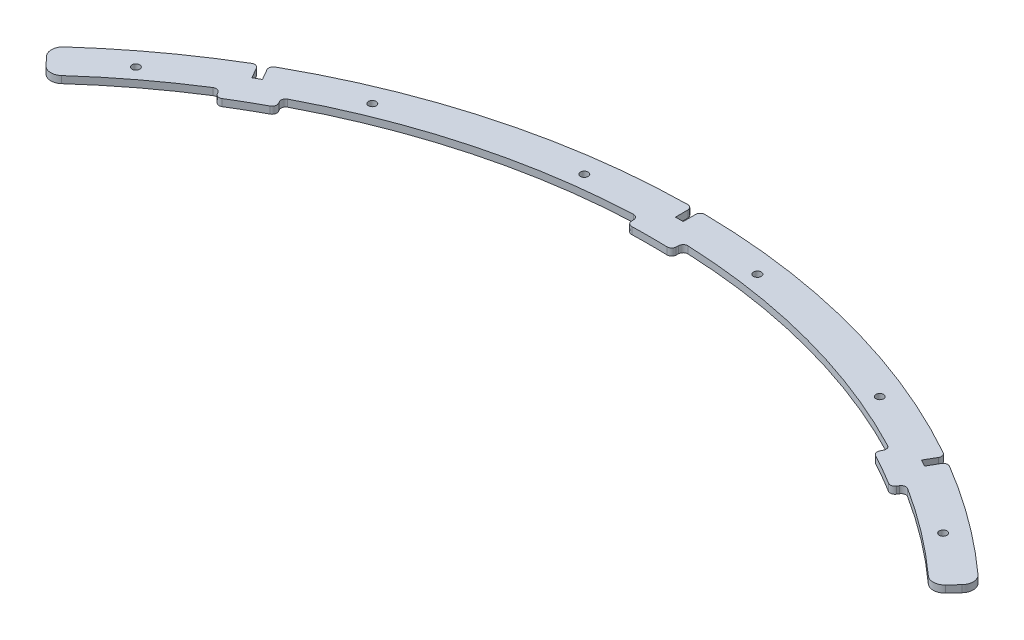
SolidWorks part; units mm, degrees
ref_plane "Front Plane" through (0, 0, 0) normal (0, 0, 1) x (1, 0, 0)
ref_plane "Top Plane" through (0, 0, 0) normal (0, 1, 0) x (1, 0, 0)
ref_plane "Right Plane" through (0, 0, 0) normal (1, 0, 0) x (0, 0, -1)
sketch "Sketch1" plane through (0, 0, 0) normal (0, 1, 0) x (1, 0, 0)
  line L0 (0, 0) -> (0, 291.5) construction
  line L1 (-145.75, 252.4464) -> (0, 0) construction
  line L2 (0, 0) -> (145.75, 252.4464) construction
  line L3 (-147.1766, 251.6174) -> (-143.5289, 245.2994)
  line L4 (-143.5289, 245.2994) -> (-140.6711, 246.9494)
  line L5 (-140.6711, 246.9494) -> (-144.3187, 253.2674)
  line L6 (-1.65, 291.4953) -> (-1.65, 284.2)
  line L7 (1.65, 284.2) -> (1.65, 291.4953)
  line L8 (-1.65, 284.2) -> (1.65, 284.2)
  line L9 (144.3187, 253.2674) -> (140.6711, 246.9494)
  line L10 (143.5289, 245.2994) -> (147.1766, 251.6174)
  line L11 (140.6711, 246.9494) -> (143.5289, 245.2994)
  line L12 (-154.4715, 247.206) -> (-143.8731, 230.2451)
  line L13 (-127.4615, 239.7203) -> (-129.8089, 244.135)
  line L14 (154.4715, 247.206) -> (143.8731, 230.2451)
  line L15 (127.4615, 239.7203) -> (129.8089, 244.135)
  line L16 (9.4752, 271.3346) -> (9.6497, 276.3316)
  line L17 (-9.6497, 276.3316) -> (-9.4752, 271.3346)
  circle A0 centre (0, 0) radius 291.5 construction
  circle A1 centre (0, 0) radius 284.5 construction
  arc A2 (1.65, 291.4953) -> (144.3187, 253.2674) centre (0, 0) cw
  arc A3 (-144.3187, 253.2674) -> (-1.65, 291.4953) centre (0, 0) cw
  arc A4 (-129.8089, 244.135) -> (-9.6497, 276.3316) centre (0, 0) cw
  arc A5 (-147.1766, 251.6174) -> (-154.4715, 247.206) centre (0, 0) ccw
  arc A6 (147.1766, 251.6174) -> (154.4715, 247.206) centre (0, 0) cw
  arc A7 (-143.8731, 230.2451) -> (-127.4615, 239.7203) centre (0, 0) cw
  arc A8 (143.8731, 230.2451) -> (127.4615, 239.7203) centre (0, 0) ccw
  arc A9 (-9.4752, 271.3346) -> (9.4752, 271.3346) centre (0, 0) cw
  arc A10 (9.6497, 276.3316) -> (129.8089, 244.135) centre (0, 0) cw
  point P12 (-142.25, 246.3842)
  point P23 (0, 0)
  point P41 (0, 0)
  dimension "D1" = 583
  dimension "D2" = 569
  dimension "D3" = 30
  dimension "D4" = 30
  dimension "D5" = 0.3
  dimension "D6" = 1.65
  dimension "D7" = 1.65
  dimension "D9" = 15
  dimension "D10" = 2
  dimension "D11" = 20
  dimension "D12" = 2
  dimension "D8" = 3
  dimension "D13" = 2
extrude "Boss-Extrude1" add sketch "Sketch1" along normal blind 3
fillet "Fillet1" radius 2 8 edges at (127.4615, 1.5, -239.7203) (129.8089, 1.5, -244.135) (-127.4615, 1.5, -239.7203) (-129.8089, 1.5, -244.135) (-9.6497, 1.5, -276.3316) (-9.4752, 1.5, -271.3346) (9.4752, 1.5, -271.3346) (9.6497, 1.5, -276.3316)
fillet "Fillet2" radius 2 4 edges at (-154.4715, 1.5, -247.206) (-143.8731, 1.5, -230.2451) (154.4715, 1.5, -247.206) (143.8731, 1.5, -230.2451)
fillet "Fillet3" radius 2 6 edges at (147.1766, 1.5, -251.6174) (144.3187, 1.5, -253.2674) (-1.65, 1.5, -291.4953) (1.65, 1.5, -291.4953) (-144.3187, 1.5, -253.2674) (-147.1766, 1.5, -251.6174)
sketch "Sketch2" plane through (0, 3, 0) normal (0, 1, 0) x (1, 0, 0)
  line L0 (-152.76, 248.2673) -> (-146.5227, 234.4853)
  line L1 (-191.9523, 205.8436) -> (-195.3628, 209.5009)
  line L2 (-145.75, 252.4464) -> (0, 0) construction
  line L3 (-153.408, 245.5041) -> (-144.929, 231.935) construction
  line L4 (0, -1000) -> (0, 49000) construction
  line L5 (191.9523, 205.8436) -> (195.3628, 209.5009)
  line L6 (152.76, 248.2673) -> (146.5227, 234.4853)
  arc A0 (-152.76, 248.2673) -> (-195.0517, 216.6266) centre (0, 0) ccw
  circle A1 centre (0, 0) radius 291.5 construction
  arc A2 (-146.5227, 234.4853) -> (-184.951, 205.5368) centre (0, 0) ccw
  arc A3 (-9.6497, 276.3316) -> (-129.8089, 244.135) centre (0, 0) ccw construction
  arc A5 (-195.0517, 216.6266) -> (-195.3628, 209.5009) centre (-191.706, 212.9109) ccw
  arc A6 (-184.951, 205.5368) -> (-191.9523, 205.8436) centre (-188.2955, 209.2536) cw
  arc A7 (184.951, 205.5368) -> (191.9523, 205.8436) centre (188.2955, 209.2536) ccw
  arc A8 (195.0517, 216.6266) -> (195.3628, 209.5009) centre (191.706, 212.9109) cw
  arc A9 (146.5227, 234.4853) -> (184.951, 205.5368) centre (0, 0) cw
  arc A10 (152.76, 248.2673) -> (195.0517, 216.6266) centre (0, 0) cw
  dimension "D2" = 5
  dimension "D1" = 13
extrude "Boss-Extrude2" add sketch "Sketch2" against normal up to surface (3 mm away) up to face at (0, 0, -257.126)
fillet "Fillet4" radius 2 2 edges at (-146.5227, 1.5, -234.4853) (146.5227, 1.5, -234.4853)
sketch "Sketch3" plane through (0, 3, 0) normal (0, 1, 0) x (1, 0, 0)
  line L0 (0, 0) -> (0, 283) construction
  line L1 (-36.9389, 280.5789) -> (0, 0) construction
  line L2 (0, 0) -> (36.9389, 280.5789) construction
  line L3 (0, 0) -> (108.2994, 261.4579) construction
  line L4 (0, 0) -> (-108.2994, 261.4579) construction
  line L5 (172.2795, 224.519) -> (0, 0) construction
  line L6 (0, 0) -> (-172.2795, 224.519) construction
  circle A0 centre (0, 0) radius 283 construction
  circle A1 centre (-36.9389, 280.5789) radius 1.65
  circle A2 centre (36.9389, 280.5789) radius 1.65
  circle A3 centre (108.2994, 261.4579) radius 1.65
  circle A4 centre (-108.2994, 261.4579) radius 1.65
  circle A5 centre (172.2795, 224.519) radius 1.65
  circle A6 centre (-172.2795, 224.519) radius 1.65
  point P17 (0, 0)
  dimension "D1" = 566
  dimension "D4" = 3.3
  dimension "D2" = 7.5
  dimension "D3" = 7.5
  dimension "D5" = 15
  dimension "D6" = 15
  dimension "D7" = 15
  dimension "D8" = 15
extrude "Cut-Extrude1" cut sketch "Sketch3" against normal blind 10
equation "\"D4@Sketch1\"=\"D3@Sketch1\""
equation "\"D7@Sketch1\"=\"D6@Sketch1\""
equation "\"D2@Sketch3\"=\"D3@Sketch3\""
